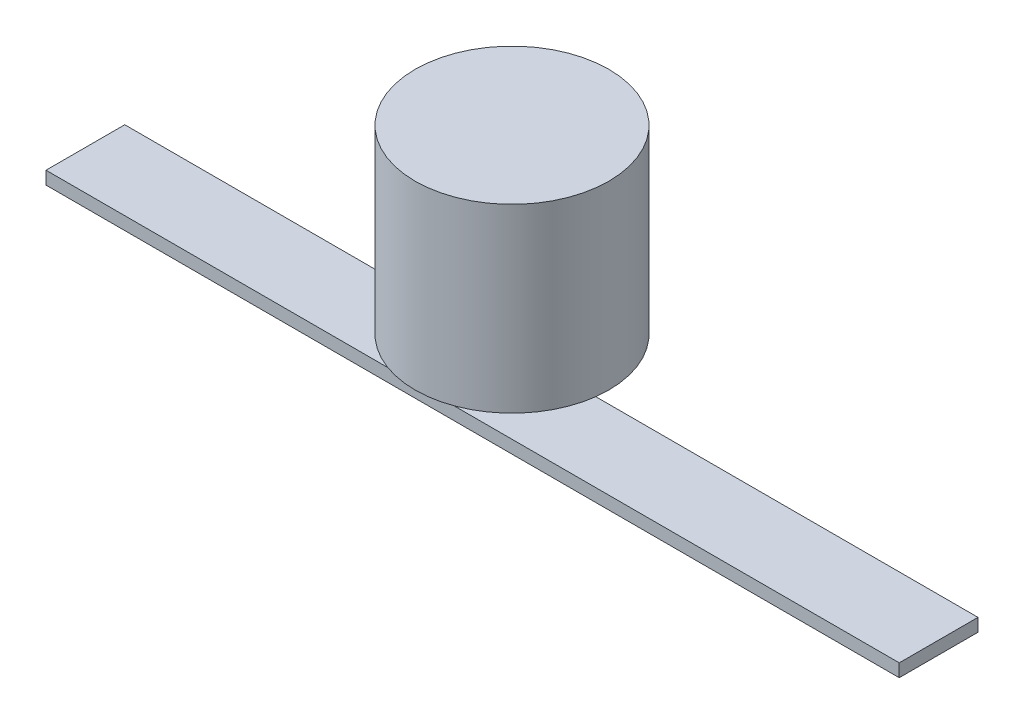
SolidWorks part; units mm, degrees
ref_plane "Front Plane" through (0, 0, 0) normal (0, 0, 1) x (1, 0, 0)
ref_plane "Top Plane" through (0, 0, 0) normal (0, 1, 0) x (1, 0, 0)
ref_plane "Right Plane" through (0, 0, 0) normal (1, 0, 0) x (0, 0, -1)
sketch "Sketch1" plane through (0, 0, 0) normal (0, 1, 0) x (1, 0, 0)
  line L1 (-165.1, -15.24) -> (165.1, -15.24)
  line L2 (-165.1, -15.24) -> (-165.1, 15.24)
  line L3 (-165.1, 15.24) -> (165.1, 15.24)
  line L4 (165.1, -15.24) -> (165.1, 15.24)
  line L5 (-165.1, -15.24) -> (165.1, 15.24) construction
  line L6 (-165.1, 15.24) -> (165.1, -15.24) construction
  point P0 (0, 0)
  dimension "D1" = 330.2
  dimension "D2" = 30.48
extrude "Boss-Extrude1" add sketch "Sketch1" along normal blind 5
sketch "Sketch2" plane through (0, 5, 0) normal (0, 1, 0) x (1, 0, 0)
  circle A0 centre (0, 0) radius 7.5
  dimension "D1" = 15
extrude "Boss-Extrude2" add sketch "Sketch2" along normal blind 20
sketch "Sketch3" plane through (0, 25, 0) normal (0, 1, 0) x (1, 0, 0)
  circle A0 centre (0, 0) radius 37.5
  dimension "D1" = 75
extrude "Boss-Extrude3" add sketch "Sketch3" along normal blind 70
